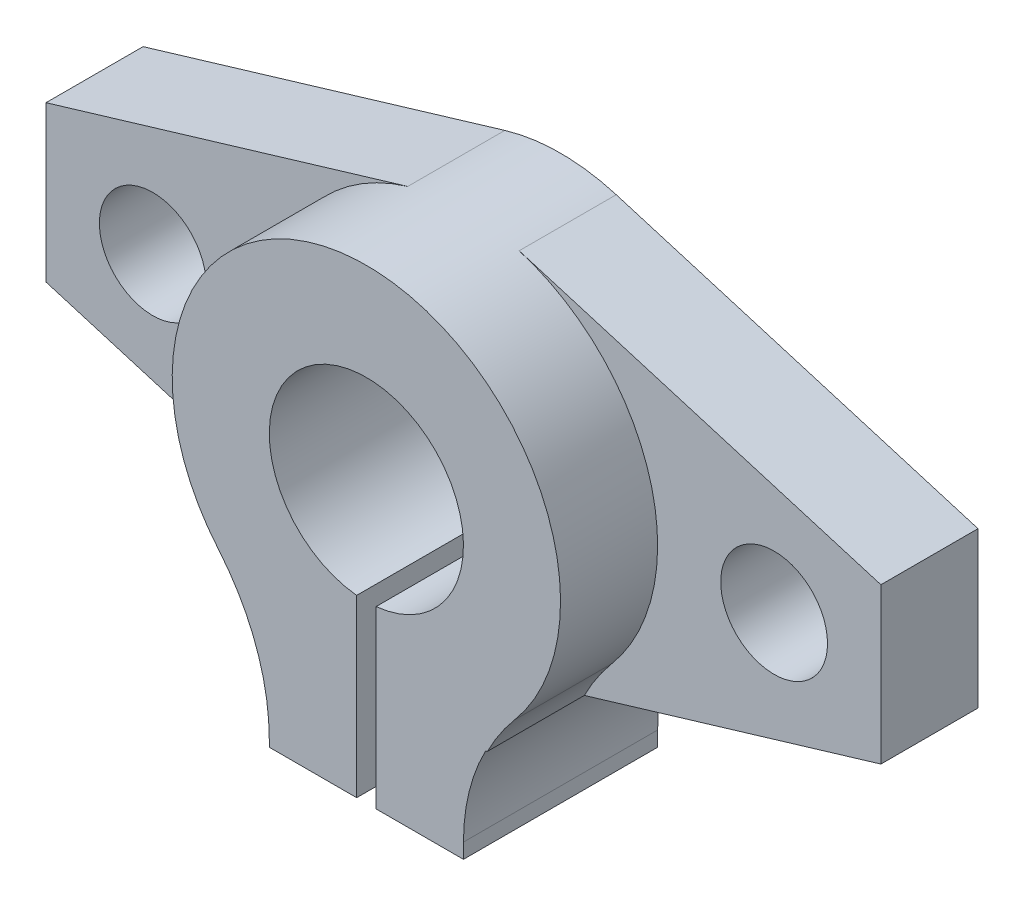
SolidWorks part; units mm, degrees
ref_plane "Спереди" through (0, 0, 0) normal (0, 0, 1) x (1, 0, 0)
ref_plane "Сверху" through (0, 0, 0) normal (0, 1, 0) x (1, 0, 0)
ref_plane "Справа" through (0, 0, 0) normal (1, 0, 0) x (0, 0, -1)
sketch "Эскиз1" plane through (0, 0, 0) normal (0, 0, 1) x (1, 0, 0)
  line L0 (-24.3559, 0) -> (32.6237, 0) construction
  line L1 (0, 21.4119) -> (0, -29.1651) construction
  line L2 (0, 0) -> (-16, 0)
  line L3 (0, 0) -> (-21.5, 0)
  line L4 (-21.5, -4) -> (-21.5, 4)
  line L5 (21.5, -4) -> (21.5, 4)
  line L6 (-21.5, 4) -> (-2.8689, 9.5796)
  line L7 (21.5, 4) -> (2.8689, 9.5796)
  line L8 (-21.5, -4) -> (-6.2262, -8.5742)
  line L9 (21.5, -4) -> (6.135, -8.6015)
  line L10 (0, 10) -> (0, 0)
  line L11 (5, -14) -> (0.5, -14)
  line L12 (-5, -14) -> (-5, -13.6598)
  line L13 (5, -14) -> (5, -13.2288)
  line L15 (-0.5, -14) -> (-0.5, -5.1644)
  line L16 (0.5, -14) -> (0.5, -5.1644)
  line L18 (-0.5, -14) -> (-5, -14)
  arc A0 (7.5, -6.6144) -> (-7.6369, -6.4558) centre (0, 0) ccw
  arc A1 (0.5, -5.1644) -> (-0.5, -5.1644) centre (0, 0) ccw
  circle A2 centre (-16, 0) radius 2.75
  circle A3 centre (16, 0) radius 2.75
  arc A4 (7.5, -6.6144) -> (5, -13.2288) centre (15, -13.2288) ccw
  arc A5 (-7.6369, -6.4558) -> (-5, -13.6598) centre (-16.1589, -13.6598) cw
  point P20 (0, 10)
  dimension "D1" = 16
  dimension "D2" = 5.5
  dimension "D6" = 20
  dimension "D9" = 10
  dimension "D10" = 11.1589
  dimension "D3" = 21.5
  dimension "D4" = 4
extrude "Бобышка-Вытянуть4" add sketch "Эскиз1" along normal blind 5 contours A2 L3 A0 L6 L4 | A5 A0 L3 A2 L4 L8 | A0 A4 L9 L5 L7 A3
sketch "Эскиз5" plane through (0, 0, 5) normal (0, 0, 1) x (1, 0, 0)
  line L0 (-0.5, -14) -> (-5, -14)
  line L1 (-5, -14) -> (-5, -13.6598)
  line L2 (-0.5, -14) -> (-0.5, -5.1644)
  line L3 (0.5, -5.1644) -> (0.5, -14)
  line L4 (0.5, -14) -> (5, -14)
  line L5 (5, -14) -> (5, -13.6598)
  arc A0 (7.6369, -6.4558) -> (-7.6369, -6.4558) centre (0, 0) ccw
  circle A1 centre (0, 0) radius 5.1886
  arc A3 (7.6369, -6.4558) -> (5, -13.6598) centre (16.1589, -13.6598) ccw
  arc A4 (-5, -13.6598) -> (-7.6369, -6.4558) centre (-16.1589, -13.6598) ccw
  arc M3 (2.8689, 9.5796) -> (-2.8689, 9.5796) centre (0, 0) ccw
  arc M7 (-6.2262, -8.5742) -> (-5, -13.6598) centre (-16.1589, -13.6598) cw
  line M8 (-5, -13.6598) -> (-5, -14)
  line M9 (-5, -14) -> (-0.5, -14)
  line M10 (-0.5, -14) -> (-0.5, -5.1644)
  arc M11 (-0.5, -5.1644) -> (0.5, -5.1644) centre (0, 0) cw
  line M12 (0.5, -5.1644) -> (0.5, -14)
  line M13 (0.5, -14) -> (5, -14)
  line M14 (5, -14) -> (5, -13.2288)
  arc M15 (5, -13.2288) -> (6.135, -8.6015) centre (15, -13.2288) cw
  line M16 (6.135, -8.6015) -> (21.5, -4)
  dimension "D1" = 20
  dimension "D3" = 11.1589
extrude "Бобышка-Вытянуть5" add sketch "Эскиз5" along normal blind 5 contours A4 A3 A0 M7 M8 M9 M10 M11 M12 M13 M14 M15 M16 M3
sketch "Эскиз6" plane through (0, 0, 10) normal (0, 0, 1) x (1, 0, 0)
  circle A0 centre (0, 0) radius 5.1886
extrude "Бобышка-Вытянуть6" add sketch "Эскиз6" against normal blind 10
sketch "Эскиз7" plane through (0, 0, 10) normal (0, 0, 1) x (1, 0, 0)
  line L0 (-0.5, -5.1644) -> (-0.5, -4.9749)
  line L1 (0.5, -5.1644) -> (0.5, -4.9749)
  arc A0 (0.5, -4.9749) -> (-0.5, -4.9749) centre (0, 0) ccw
  dimension "D1" = 10
extrude "Вырез-Вытянуть1" cut sketch "Эскиз7" against normal through all and the other way through all
sketch "Эскиз8" plane through (0, 0, 5) normal (0, 0, 1) x (1, 0, 0)
  line L0 (-21.5, -4) -> (-21.5, 4) construction
  line L2 (21.5, -4) -> (21.5, 4) construction
  arc A0 (7.6369, -6.4558) -> (-7.6369, -6.4558) centre (0, 0) ccw construction
  arc A1 (2.8689, 9.5796) -> (-2.8689, 9.5796) centre (0, 0) ccw construction
  point P5 (-16, 0)
  point P10 (0, 0)
  point P11 (-21.5, 0)
  point P12 (0, 10)
  point P19 (21.5, 0)
